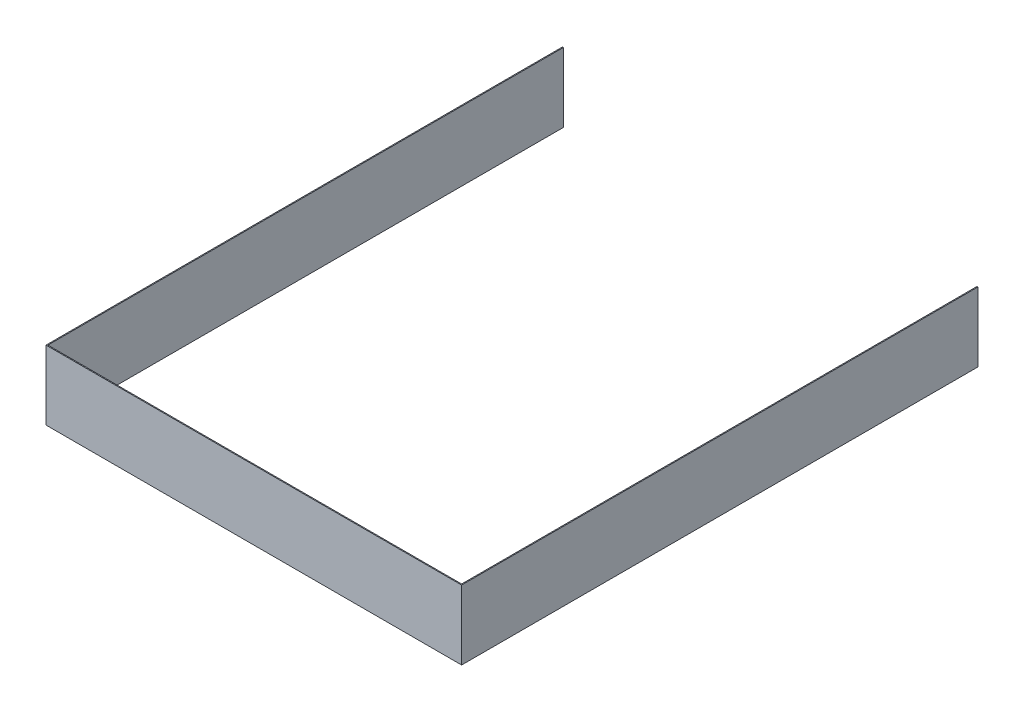
SolidWorks part; units mm, degrees
ref_plane "Front Plane" through (0, 0, 0) normal (0, 0, 1) x (1, 0, 0)
ref_plane "Top Plane" through (0, 0, 0) normal (0, 1, 0) x (1, 0, 0)
ref_plane "Right Plane" through (0, 0, 0) normal (1, 0, 0) x (0, 0, -1)
other "Configuration Table"
sketch "Sketch1" plane through (0, 0, 0) normal (0, 1, 0) x (1, 0, 0)
  line L0 (20, 800) -> (20, -20)
  line L1 (20, -20) -> (680, -20)
  line L2 (680, -20) -> (680, 800)
  line L3 (680, 800) -> (678.5, 800)
  line L4 (678.5, 800) -> (678.5, -18.5)
  line L5 (678.5, -18.5) -> (21.5, -18.5)
  line L6 (21.5, -18.5) -> (21.5, 800)
  line L7 (21.5, 800) -> (20, 800)
extrude "OVEN_plint_U_1" add sketch "Sketch1" along normal blind 110 from offset 10 separate body
